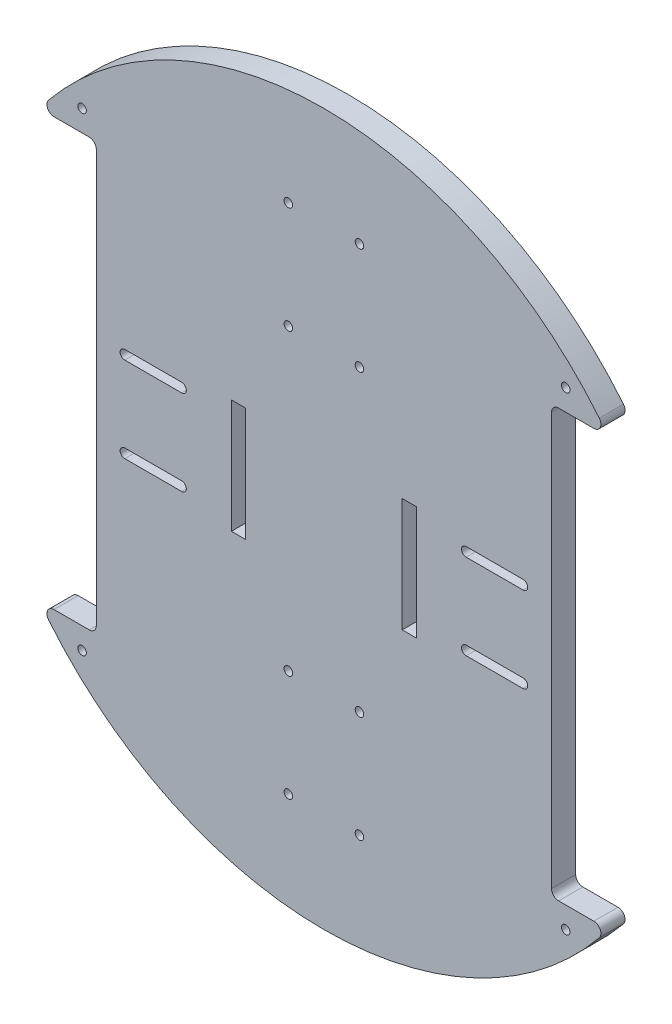
SolidWorks part; units mm, degrees
ref_plane "Piano frontale" through (0, 0, 0) normal (0, 0, 1) x (1, 0, 0)
ref_plane "Piano superiore" through (0, 0, 0) normal (0, 1, 0) x (1, 0, 0)
ref_plane "Piano destro" through (0, 0, 0) normal (1, 0, 0) x (0, 0, -1)
sketch "Schizzo1" plane through (0, 0, 0) normal (0, 0, 1) x (1, 0, 0)
  line L0 (0, 0) -> (50000, 0) construction
  line L1 (0, 0) -> (0, 50000) construction
  line L2 (240, 150) -> (240, -150)
  line L3 (-240, 150) -> (-160, 150)
  line L4 (-240, 150) -> (-240, -150)
  line L5 (-240, -150) -> (-160, -150)
  line L6 (-160, 150) -> (-160, -150)
  line L7 (-240, 150) -> (-160, -150) construction
  line L8 (-240, -150) -> (-160, 150) construction
  line L9 (240, -150) -> (160, -150)
  line L10 (160, 150) -> (160, -150)
  line L11 (240, 150) -> (160, 150)
  circle A0 centre (0, 0) radius 250
  point P3 (-200, 0)
  dimension "D1" = 500
  dimension "D2" = 300
  dimension "D3" = 80
  dimension "D4" = 200
extrude "Estrusione-Estrusione1" add sketch "Schizzo1" along normal blind 17 contours L11 A0 L3 L6 L5 L9 L10
sketch "Schizzo2" plane through (0, 0, 17) normal (0, 0, 1) x (1, 0, 0)
  line L0 (0, 0) -> (50000, 0) construction
  line L1 (-160, 30) -> (49840, 30) construction
  line L3 (-140, 30) -> (-100, 30) construction
  line L4 (-140, 33.25) -> (-100, 33.25)
  line L5 (-140, 26.75) -> (-100, 26.75)
  line L6 (-160, 150) -> (-160, -150) construction
  line L7 (-140, -30) -> (-100, -30) construction
  line L8 (-140, -33.25) -> (-100, -33.25)
  line L9 (-140, -26.75) -> (-100, -26.75)
  line L10 (0, 0) -> (0, 50000) construction
  line L11 (140, -30) -> (100, -30) construction
  line L12 (140, -33.25) -> (100, -33.25)
  line L13 (140, -26.75) -> (100, -26.75)
  line L14 (140, 30) -> (100, 30) construction
  line L15 (140, 33.25) -> (100, 33.25)
  line L16 (140, 26.75) -> (100, 26.75)
  arc A0 (-140, 33.25) -> (-140, 26.75) centre (-140, 30) ccw
  arc A1 (-100, 26.75) -> (-100, 33.25) centre (-100, 30) ccw
  arc A2 (-140, -33.25) -> (-140, -26.75) centre (-140, -30) cw
  arc A3 (-100, -26.75) -> (-100, -33.25) centre (-100, -30) cw
  arc A4 (140, -33.25) -> (140, -26.75) centre (140, -30) ccw
  arc A5 (100, -26.75) -> (100, -33.25) centre (100, -30) ccw
  arc A6 (140, 33.25) -> (140, 26.75) centre (140, 30) cw
  arc A7 (100, 26.75) -> (100, 33.25) centre (100, 30) cw
  point P7 (-120, 30)
  point P16 (-120, -30)
  point P25 (120, -30)
  point P32 (120, 30)
  dimension "D1" = 30
  dimension "D2" = 40
  dimension "D3" = 40
  dimension "D4" = 6.5
extrude "Taglio-Estrusione1" cut sketch "Schizzo2" against normal through all
fillet "Raccordo1" radius 5 8 edges at (-200, -150, 8.5) (-160, -150, 8.5) (200, -150, 8.5) (160, -150, 8.5) (200, 150, 8.5) (160, 150, 8.5) (-200, 150, 8.5) (-160, 150, 8.5)
sketch "Schizzo3" plane through (0, 0, 0) normal (0, 0, -1) x (-1, 0, 0)
  line L0 (0, 0) -> (0, 50000) construction
  line L1 (-69.4268, 180) -> (49930.5732, 180) construction
  line L2 (-57.7475, 105) -> (49942.2525, 105) construction
  line L3 (0, 0) -> (50000, 0) construction
  circle A0 centre (-25, 180) radius 3
  circle A1 centre (25, 180) radius 3
  circle A2 centre (-25, 105) radius 3
  circle A3 centre (25, 105) radius 3
  circle A4 centre (-25, -105) radius 3
  circle A5 centre (25, -105) radius 3
  circle A6 centre (25, -180) radius 3
  circle A7 centre (-25, -180) radius 3
  dimension "D4" = 6
  dimension "D1" = 180
  dimension "D2" = 75
  dimension "D3" = 25
  dimension "D5" = 50
extrude "Taglio-Estrusione2" cut sketch "Schizzo3" against normal through all
sketch "Schizzo4" plane through (0, 0, 0) normal (0, 0, -1) x (-1, 0, 0)
  line L0 (0, 0) -> (0, 50000) construction
  line L1 (-65, 40) -> (-55, 40)
  line L2 (-65, 40) -> (-65, -40)
  line L3 (-65, -40) -> (-55, -40)
  line L4 (-55, 40) -> (-55, -40)
  line L5 (-65, 40) -> (-55, -40) construction
  line L6 (-65, -40) -> (-55, 40) construction
  line L7 (65, -40) -> (55, 40) construction
  line L8 (65, 40) -> (55, -40) construction
  line L9 (55, 40) -> (55, -40)
  line L10 (65, -40) -> (55, -40)
  line L11 (65, 40) -> (65, -40)
  line L12 (65, 40) -> (55, 40)
  point P0 (-60, 0)
  point P12 (60, 0)
  dimension "D1" = 10
  dimension "D2" = 60
  dimension "D3" = 80
extrude "Taglio-Estrusione4" cut sketch "Schizzo4" against normal through all
sketch "Schizzo5" plane through (0, 0, 0) normal (0, 0, -1) x (-1, 0, 0)
  line L0 (0, 0) -> (50000, 0) construction
  line L1 (-148.9107, 165) -> (49851.0893, 165) construction
  line L2 (-170, 160) -> (-170, -49840) construction
  line L3 (0, 0) -> (0, 50000) construction
  circle A0 centre (-170, 165) radius 3
  circle A1 centre (170, 165) radius 3
  circle A2 centre (170, -165) radius 3
  circle A3 centre (-170, -165) radius 3
  dimension "D3" = 6
  dimension "D1" = 165
  dimension "D2" = 170
extrude "Taglio-Estrusione5" cut sketch "Schizzo5" against normal through all
